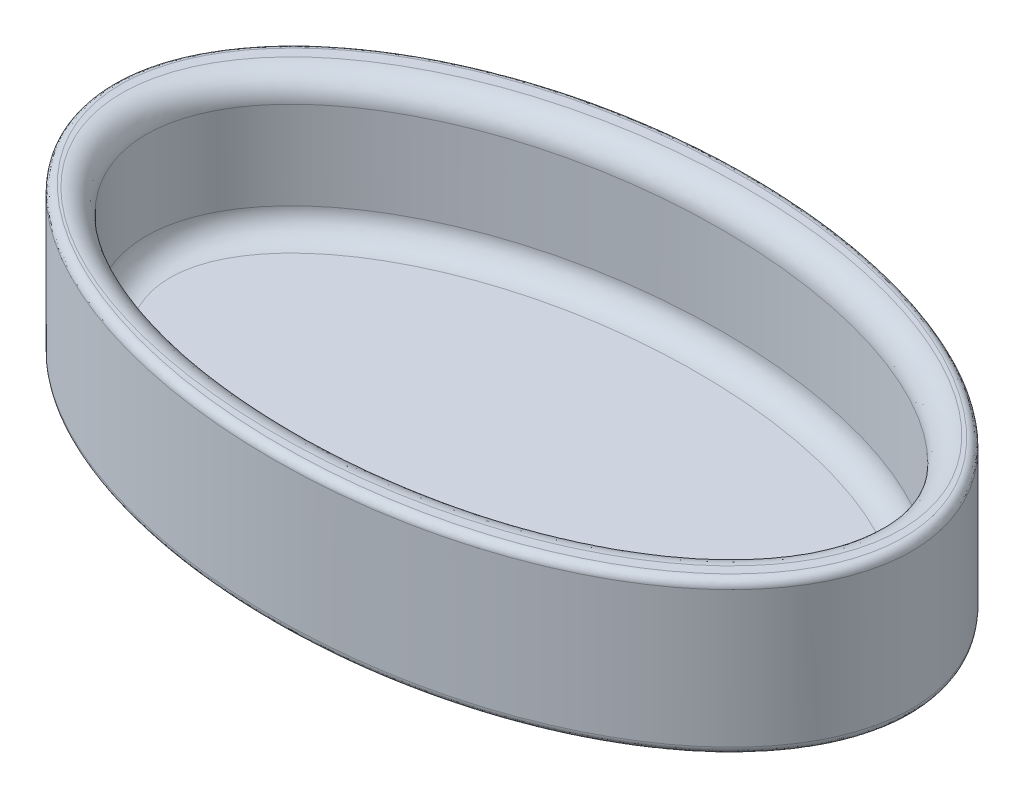
SolidWorks part; units mm, degrees
ref_plane "Alzado" through (0, 0, 0) normal (0, 0, 1) x (1, 0, 0)
ref_plane "Planta" through (0, 0, 0) normal (0, 1, 0) x (1, 0, 0)
ref_plane "Vista lateral" through (0, 0, 0) normal (1, 0, 0) x (0, 0, -1)
sketch "Sketch2" plane through (0, 0, 0) normal (0, 1, 0) x (1, 0, 0)
  line L0 (0, 0) -> (100, 0) construction
  line L1 (100, 0) -> (100, 100) construction
  line L2 (100, 100) -> (0, 100) construction
  line L3 (0, 100) -> (0, 0) construction
  ellipse E0 centre (50.0001, 50.0819) end of major axis (0.0001, 50.1638) minor radius 30
  dimension "D1" = 100
  dimension "D2" = 100
extrude "Boss-Extrude1" add sketch "Sketch2" along normal blind 19.05 contours E0
sketch "Sketch3" plane through (0, 19.05, 0) normal (0, 1, 0) x (1, 0, 0)
  ellipse E0 centre (50, 50) end of major axis (94.989, 50.9948) minor radius 25
extrude "Cut-Extrude1" cut sketch "Sketch3" against normal blind 17
fillet "Fillet1" radius 3 1 edges at (94.989, 2.05, -50.9948)
fillet "Fillet2" radius 3 1 edges at (94.989, 19.05, -50.9948)
fillet "Fillet4" radius 1 1 edges at (100, 19.05, -50)
fillet "Fillet5" radius 1 1 edges at (100, 0, -50)
